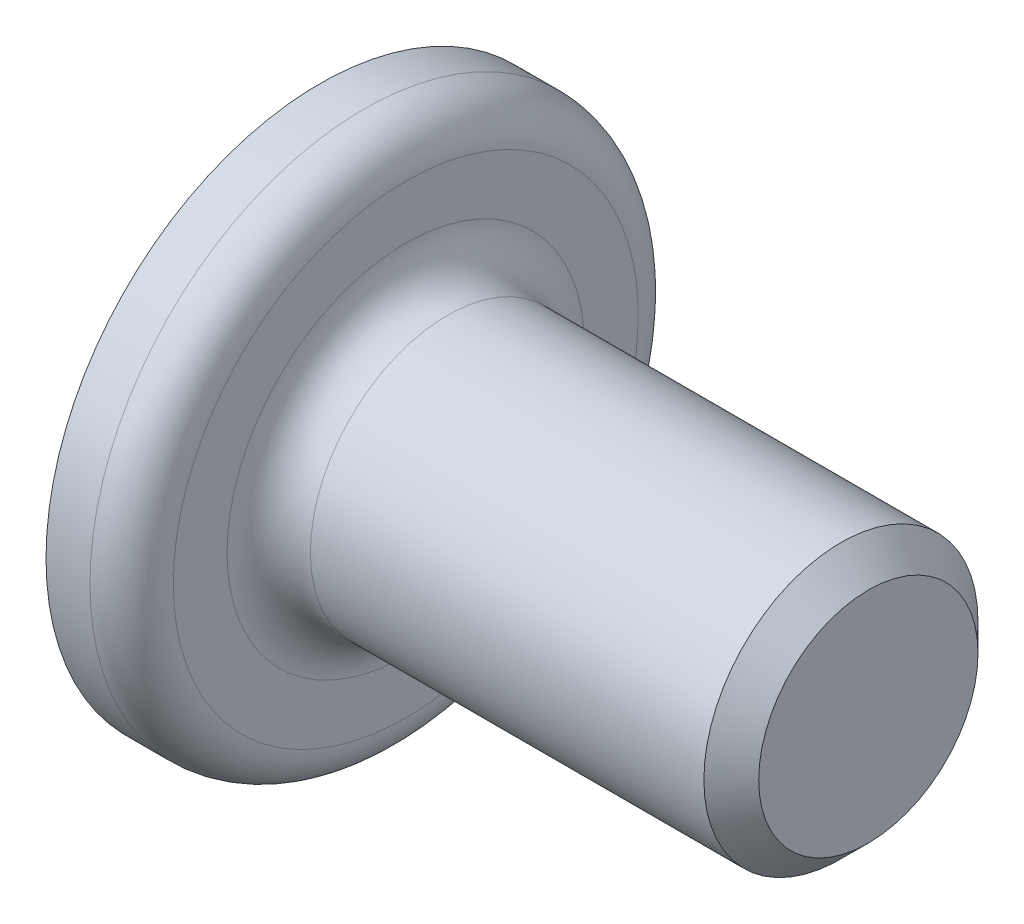
SolidWorks part; units mm, degrees
ref_plane "Front" through (0, 0, 0) normal (0, 0, 1) x (1, 0, 0)
ref_plane "Top" through (0, 0, 0) normal (0, 1, 0) x (1, 0, 0)
ref_plane "Right" through (0, 0, 0) normal (1, 0, 0) x (0, 0, -1)
sketch "Sketch1" plane through (0, 0, 0) normal (0, 0, 1) x (1, 0, 0)
  line L0 (0, 0) -> (0, 6.35)
  line L1 (0, 6.35) -> (1.9844, 6.35)
  line L2 (1.9844, 6.35) -> (1.9844, 3.175)
  line L3 (1.9844, 3.175) -> (12.7, 3.175)
  line L4 (12.7, 3.175) -> (12.7, 0)
  line L5 (0, 0) -> (12.7, 0) construction
  line L6 (0, 0) -> (12.7, 0)
  dimension "Base Diameter" = 12.7
  dimension "Shaft Diameter" = 6.35
  dimension "Base Thickness" = 1.9844
  dimension "D1" = 12.7
revolve "Revolve1" add sketch "Sketch1" angle 360 about L5
chamfer "Chamfer1" distance 0.635 angle 45 1 edges at (12.7, 0, 3.175)
sketch "Sketch4" plane through (0, 0, 0) normal (0, 0, 1) x (1, 0, 0)
  line L0 (1.9844, 3.175) -> (1.9844, 6.35) construction
  line L1 (1.9844, -3.175) -> (1.9844, 3.175) construction
  line L2 (1.9844, -6.35) -> (1.9844, 6.35) construction
  line L3 (1.9844, 4.7625) -> (0, 4.7625) construction
  line L4 (0, 6.35) -> (0, -6.35) construction
  line L5 (1.9844, 4.7625) -> (1.9844, 5.969)
  line L6 (1.9844, 4.7625) -> (2.9496, 4.7625)
  line L7 (0.9922, 4.7625) -> (0.9922, 6.35) construction
  line L8 (1.9844, 6.35) -> (0, 6.35) construction
  line L9 (2.9496, 4.7625) -> (2.9496, 5.969) construction
  line L10 (0, 4.7625) -> (-0.9652, 4.7625)
  line L11 (0, 4.7625) -> (0, 5.969)
  arc A0 (2.9496, 4.7625) -> (1.9844, 5.969) centre (1.7129, 4.7625) ccw
  arc A1 (-0.9652, 4.7625) -> (0, 5.969) centre (0.2715, 4.7625) cw
  dimension "P" = 2.413
  dimension "F" = 0.9652
sketch "Sketch3" plane through (0, 0, 0) normal (0, 0, 1) x (1, 0, 0)
  line L0 (1.9844, 6.35) -> (1.9844, 3.175) construction
  line L2 (1.9844, -3.175) -> (1.9844, 3.175) construction
  line L5 (1.9844, 4.7625) -> (0, 4.7625) construction
  line L6 (0, 6.35) -> (0, -6.35) construction
  line L7 (0, 4.7625) -> (-0.9652, 4.7625)
  line L8 (0, 4.7625) -> (0, 5.969)
  line L9 (-0.9652, 4.7625) -> (-0.9652, 5.969) construction
  arc A0 (-0.9652, 4.7625) -> (0, 5.969) centre (0.2715, 4.7625) cw
  arc A1 (0, 5.969) -> (-0.9652, 4.7625) centre (0.2715, 4.7625) ccw construction
revolve "Revolve3" add sketch "Sketch3" angle 360 about L5
pattern_circular "CirPattern2" count 3 over 360 about axis through (0, 0, 0) along (1, 0, 0) of "Revolve3"
fillet "Fillet2" radius 0.9652 2 edges at (1.9844, 0, 6.35) (1.9844, 0, 3.175)
sketch "Sketch2" [suppressed] plane through (0, 0, 0) normal (0, 0, 1) x (1, 0, 0)
  line L0 (1.9844, 6.35) -> (1.9844, 2.3813) construction
  line L1 (1.9844, -2.3813) -> (1.9844, 2.3813) construction
  line L2 (1.9844, -6.35) -> (1.9844, 6.35) construction
  line L3 (1.9844, 4.3656) -> (2.8226, 4.3656)
  line L4 (1.9844, 4.3656) -> (1.9844, 5.4451)
  line L5 (1.9844, 4.3656) -> (0, 4.3656) construction
  line L6 (0, 6.35) -> (0, -6.35) construction
  line L7 (2.8226, 4.3656) -> (2.8226, 5.4451) construction
  arc A0 (2.8226, 4.3656) -> (1.9844, 5.4451) centre (1.7083, 4.3656) ccw
  point P8 (1.9844, 4.3656)
revolve "Revolve2" [suppressed] add sketch "Sketch2" angle 360 about L5
pattern_circular "CirPattern1" [suppressed] count 3 over 360
fillet "Fillet1" [suppressed] radius 0.9652
equation "\"D1@Chamfer1\" = \"Shaft Diameter@Sketch1\"*.1"
equation "\"D1@Fillet1\" = \"F@Sketch4\""
equation "\"D1@Fillet2\" = \"F@Sketch4\""
